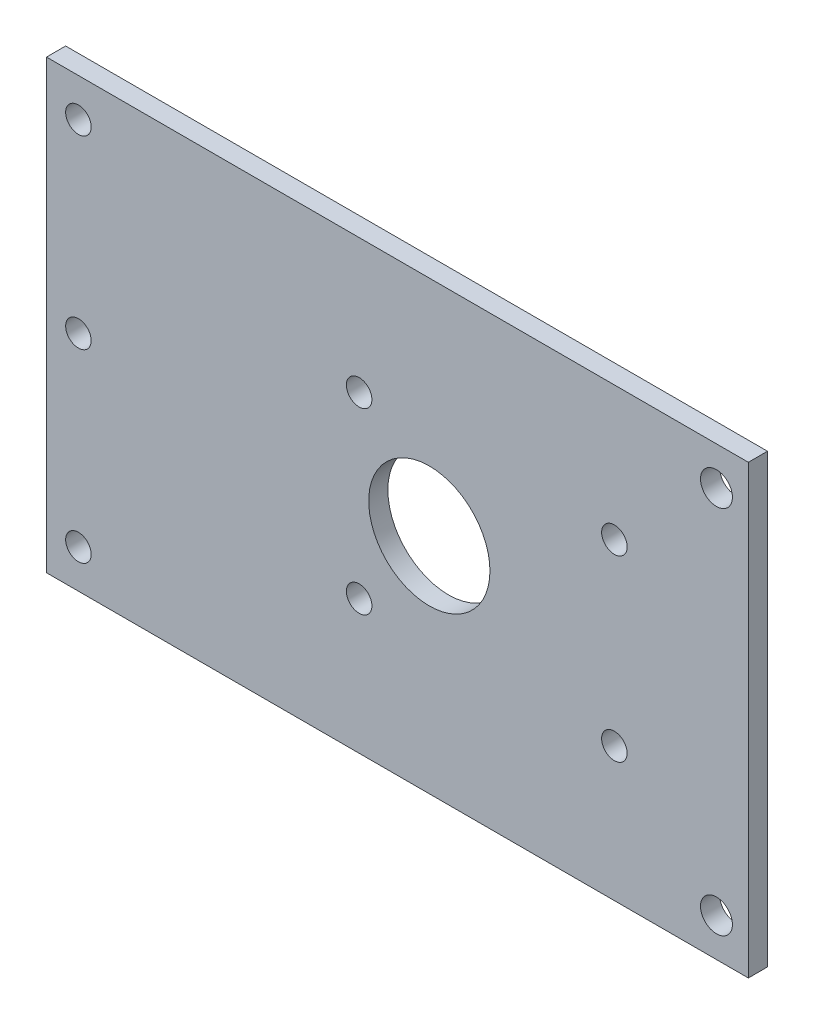
SolidWorks part; units mm, degrees
material "6061 Alloy"
ref_plane "Front Plane" through (0, 0, 0) normal (0, 0, 1) x (1, 0, 0)
ref_plane "Top Plane" through (0, 0, 0) normal (0, 1, 0) x (1, 0, 0)
ref_plane "Right Plane" through (0, 0, 0) normal (1, 0, 0) x (0, 0, -1)
sketch "Sketch1" plane through (0, 0, 0) normal (0, 0, 1) x (1, 0, 0)
  line L1 (0, 0) -> (110, 0)
  line L2 (0, 0) -> (0, 70)
  line L3 (0, 70) -> (110, 70)
  line L4 (110, 0) -> (110, 70)
  dimension "D1" = 70
  dimension "D2" = 110
extrude "Boss-Extrude1" add sketch "Sketch1" along normal blind 3
sketch "Sketch2" plane through (0, 0, 3) normal (0, 0, 1) x (1, 0, 0)
  line L0 (110, 70) -> (0, 70) construction
  line L1 (0, 70) -> (0, 0) construction
  line L2 (0, 0) -> (110, 0) construction
  line L4 (110, 0) -> (110, 70) construction
  circle A0 centre (5, 64) radius 2
  circle A1 centre (5, 6) radius 2
  circle A2 centre (105, 64) radius 2.5
  circle A3 centre (105, 6) radius 2.5
  circle A4 centre (5, 35) radius 2
  point P18 (0, 35)
  dimension "D1" = 4
  dimension "D4" = 6
  dimension "D5" = 4
  dimension "D6" = 5
  dimension "D7" = 5
  dimension "D8" = 5
  dimension "D9" = 4
  dimension "D2" = 6
  dimension "D3" = 5
extrude "Cut-Extrude1" cut sketch "Sketch2" against normal blind 5
sketch "Sketch3" plane through (0, 0, 3) normal (0, 0, 1) x (1, 0, 0)
  line L0 (110, 35) -> (0, 35) construction
  line L1 (110, 0) -> (110, 70) construction
  line L2 (0, 70) -> (0, 0) construction
  circle A0 centre (60, 35) radius 9.5
  circle A1 centre (49, 49) radius 2
  circle A2 centre (89, 49) radius 2
  circle A3 centre (89, 21) radius 2
  circle A4 centre (49, 21) radius 2
  dimension "D1" = 19
  dimension "D2" = 4
  dimension "D4" = 4
  dimension "D3" = 60
  dimension "D5" = 14
  dimension "D6" = 40
  dimension "D7" = 11
extrude "Cut-Extrude3" cut sketch "Sketch3" against normal blind 9
